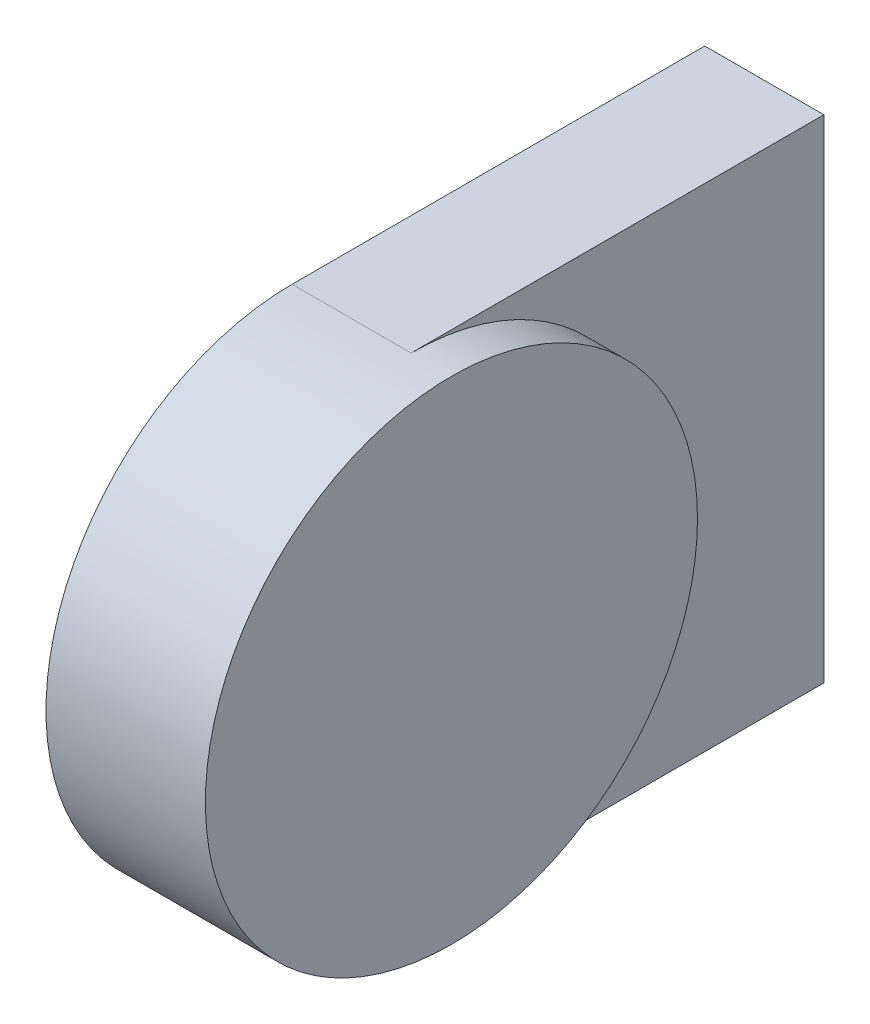
SolidWorks part; units mm, degrees
ref_plane "Front Plane" through (0, 0, 0) normal (1, 0, 0) x (0, 1, 0)
ref_plane "Top Plane" through (0, 0, 0) normal (0, 0, 1) x (0, 1, 0)
ref_plane "Right Plane" through (0, 0, 0) normal (0, 1, 0) x (-1, 0, 0)
sketch "Sketch1" plane through (0, 0, 0) normal (1, 0, 0) x (0, 1, 0)
  line L0 (0, 0) -> (0, -260) construction
  line L3 (-155, 0) -> (-155, -260)
  line L4 (-155, -260) -> (155, -260)
  line L5 (155, 0) -> (155, -260)
  arc A2 (155, 0) -> (-155, 0) centre (0, 0) ccw
  dimension "D1" = 260
  dimension "D2" = 260
  dimension "D3" = 155
extrude "Boss-Extrude1" add sketch "Sketch1" along normal blind 75 contours A2 L3 L4 L5
sketch "Sketch2" plane through (75, 0, 0) normal (1, 0, 0) x (0, 0, -1)
  circle A0 centre (0, 0) radius 155
extrude "Boss-Extrude2" add sketch "Sketch2" along normal blind 25.4 contours A0
